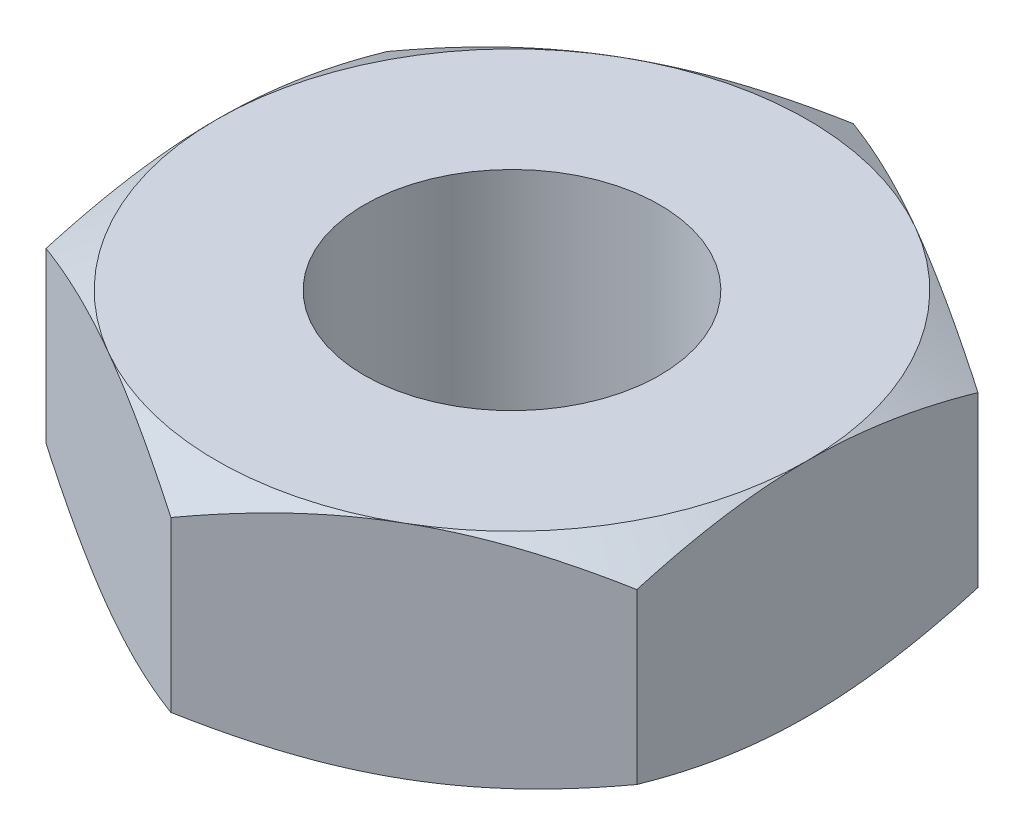
SolidWorks part; units mm, degrees
ref_plane "Front Plane" through (0, 0, 0) normal (0, 0, 1) x (1, 0, 0)
ref_plane "Top Plane" through (0, 0, 0) normal (0, 1, 0) x (1, 0, 0)
ref_plane "Right Plane" through (0, 0, 0) normal (1, 0, 0) x (0, 0, -1)
sketch "Sketch1" plane through (0, 0, 0) normal (0, 1, 0) x (1, 0, 0)
  line L1 (0, 2.3094) -> (-2, 1.1547)
  line L2 (-2, 1.1547) -> (-2, -1.1547)
  line L3 (-2, -1.1547) -> (0, -2.3094)
  line L4 (0, -2.3094) -> (2, -1.1547)
  line L5 (2, -1.1547) -> (2, 1.1547)
  line L6 (2, 1.1547) -> (0, 2.3094)
  circle A0 centre (0, 0) radius 2 construction
  circle A1 centre (0, 0) radius 1
  dimension "D1" = 2
  dimension "D2" = 4
extrude "Boss-Extrude1" add sketch "Sketch1" along normal blind 1.5
sketch "Sketch2" plane through (0, 1.5, 0) normal (0, 1, 0) x (1, 0, 0)
  circle A0 centre (0, 0) radius 2 construction
  circle A1 centre (0, 0) radius 2
extrude "Cut-Extrude1" cut sketch "Sketch2" against normal blind 2 draft 60 flip side to cut
ref_plane "Plane1" through (0, 0.75, 0) normal (0, 1, 0) x (1, 0, 0)
mirror "Mirror1" about plane through (0, 0.75, 0) normal (0, 1, 0) of "Cut-Extrude1"
